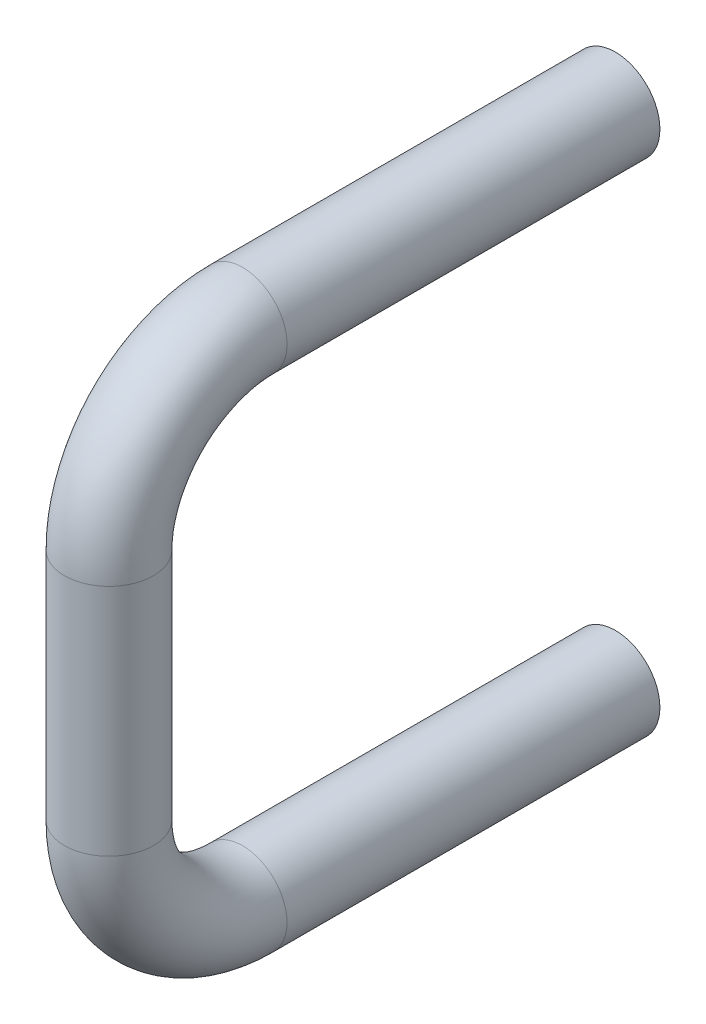
SolidWorks part; units mm, degrees
material "AISI 316 Annealed Stainless Steel Bar (SS)"
ref_plane "Front Plane" through (0, 0, 0) normal (0, 0, 1) x (1, 0, 0)
ref_plane "Top Plane" through (0, 0, 0) normal (0, 1, 0) x (1, 0, 0)
ref_plane "Right Plane" through (0, 0, 0) normal (1, 0, 0) x (0, 0, -1)
sketch3d "Pipe path 1"
  line L0 (240, -45, 323) -> (240, -45, 390)
  line L1 (240, -21, 414) -> (240, 21, 414)
  line L2 (240, 45, 390) -> (240, 45, 323)
  arc A0 (240, -45, 390) -> (240, -21, 414) centre (240, -21, 390) ccw
  arc A1 (240, 21, 414) -> (240, 45, 390) centre (240, 21, 390) ccw
  point P6 (240, -45, 414)
  point P7 (216, -21, 390)
  point P10 (240, 45, 414)
  point P11 (216, 21, 390)
  dimension "D1" = 24
  dimension "D2" = 24
sweep "Pipe 1" add path "Pipe path 1" circular profile diameter 16 parameters "D3"=16
